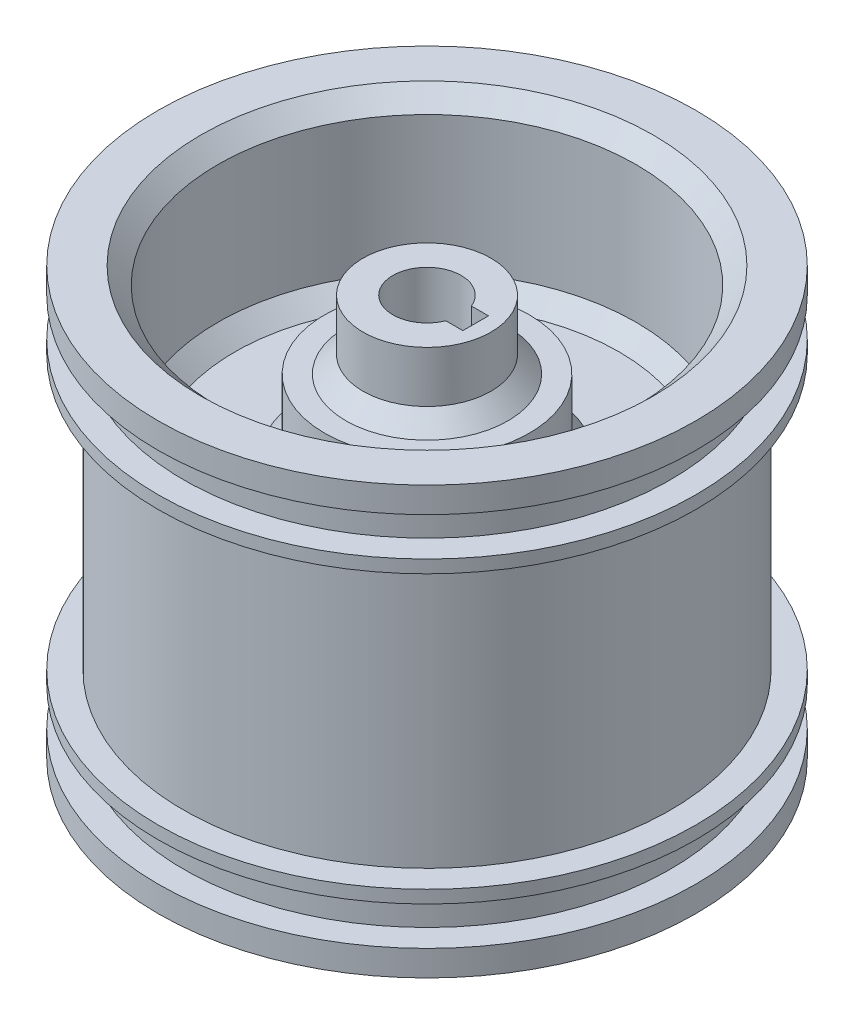
SolidWorks part; units mm, degrees
ref_plane "前视基准面" through (0, 0, 0) normal (0, 0, 1) x (1, 0, 0)
ref_plane "上视基准面" through (0, 0, 0) normal (0, 1, 0) x (1, 0, 0)
ref_plane "右视基准面" through (0, 0, 0) normal (1, 0, 0) x (0, 0, -1)
sketch "草图1" plane through (0, 0, 0) normal (0, 0, 1) x (1, 0, 0)
  line L0 (0, 0) -> (0, 33.382) construction
  line L1 (0, 0) -> (0, -38) construction
  line L3 (24.5, 0) -> (31.5, 0)
  line L4 (-24.5, 0) -> (-31.5, 0)
  line L5 (31.5, 0) -> (31.5, -3)
  line L6 (-31.5, 0) -> (-31.5, -3)
  line L7 (31.5, -3) -> (28.5, -3)
  line L8 (-31.5, -3) -> (-28.5, -3)
  line L9 (28.5, -3) -> (28.5, -7.5)
  line L10 (-28.5, -3) -> (-28.5, -7.5)
  line L11 (28.5, -7.5) -> (31.5, -7.5)
  line L12 (-28.5, -7.5) -> (-31.5, -7.5)
  line L13 (31.5, -7.5) -> (31.5, -9)
  line L14 (-31.5, -7.5) -> (-31.5, -9)
  line L15 (31.5, -9) -> (28.5, -9)
  line L16 (-31.5, -9) -> (-28.5, -9)
  line L17 (28.5, -9) -> (28.5, -41)
  line L18 (-28.5, -9) -> (-28.5, -25)
  line L19 (28.5, -25) -> (-28.5, -25) construction
  line L20 (31.5, -41) -> (28.5, -41)
  line L21 (31.5, -42.5) -> (31.5, -41)
  line L22 (28.5, -42.5) -> (31.5, -42.5)
  line L23 (28.5, -47) -> (28.5, -42.5)
  line L24 (31.5, -47) -> (28.5, -47)
  line L25 (31.5, -50) -> (31.5, -47)
  line L26 (24.5, -50) -> (31.5, -50)
  line L28 (24.5, 0) -> (24.5, -50)
  line L30 (-28.5, -20) -> (0, -20)
  line L31 (-28.5, -20) -> (-28.5, -30)
  line L32 (-28.5, -30) -> (0, -30)
  line L33 (28.5, -20) -> (28.5, -30)
  line L34 (-28.5, -20) -> (28.5, -30) construction
  line L35 (-28.5, -30) -> (28.5, -20) construction
  line L36 (10, -30) -> (10, -38)
  line L37 (10, -38) -> (0, -38)
  line L38 (0, -3) -> (0, -38)
  line L39 (12, -20) -> (12, -11)
  line L40 (12, -11) -> (7.5, -11)
  line L41 (7.5, -11) -> (7.5, -3)
  line L42 (7.5, -3) -> (0, -3)
  line L55 (12, -20) -> (24.5, -20)
  line L56 (10, -30) -> (28.5, -30)
  point P22 (0, -25)
  point P32 (0, -25)
  dimension "D1" = 49
  dimension "D2" = 63
  dimension "D3" = 3
  dimension "D4" = 57
  dimension "D5" = 4.5
  dimension "D6" = 1.5
  dimension "D7" = 63
  dimension "D8" = 57
  dimension "D9" = 25
  dimension "D11" = 8
  dimension "D12" = 12
  dimension "D13" = 10
  dimension "D14" = 9
  dimension "D15" = 7.5
  dimension "D16" = 8
  dimension "D19" = 10
revolve "旋转1" add sketch "草图1" angle 360 about L0
sketch "草图2" plane through (0, -3, 0) normal (0, 1, 0) x (1, 0, 0)
  line L0 (0, 0) -> (5.7, 0)
  line L1 (5.7, 1.5) -> (5.7, -1.5)
  line L2 (5.7, -1.5) -> (3.7081, -1.5)
  line L3 (5.7, 1.5) -> (3.7081, 1.5)
  circle A0 centre (0, 0) radius 4
  dimension "D1" = 8
  dimension "D2" = 5.7
  dimension "D3" = 1.5
extrude "切除-拉伸1" cut sketch "草图2" against normal blind 50
sketch "草图3" plane through (0, -38, 0) normal (0, -1, 0) x (1, 0, 0)
  line L1 (6.9282, 0) -> (3.4641, 6)
  line L2 (3.4641, 6) -> (-3.4641, 6)
  line L3 (-3.4641, 6) -> (-6.9282, 0)
  line L4 (-6.9282, 0) -> (-3.4641, -6)
  line L5 (-3.4641, -6) -> (3.4641, -6)
  line L6 (3.4641, -6) -> (6.9282, 0)
  circle A0 centre (0, 0) radius 6 construction
extrude "切除-拉伸2" cut sketch "草图3" against normal blind 8
chamfer "倒角1" distance 2 angle 45 7 edges at (0, -30, -10) (0, -11, -7.5) (0, -20, -12) (0, 0, -24.5) (0, -20, -24.5) (0, -30, -24.5) (0, -50, -24.5)
